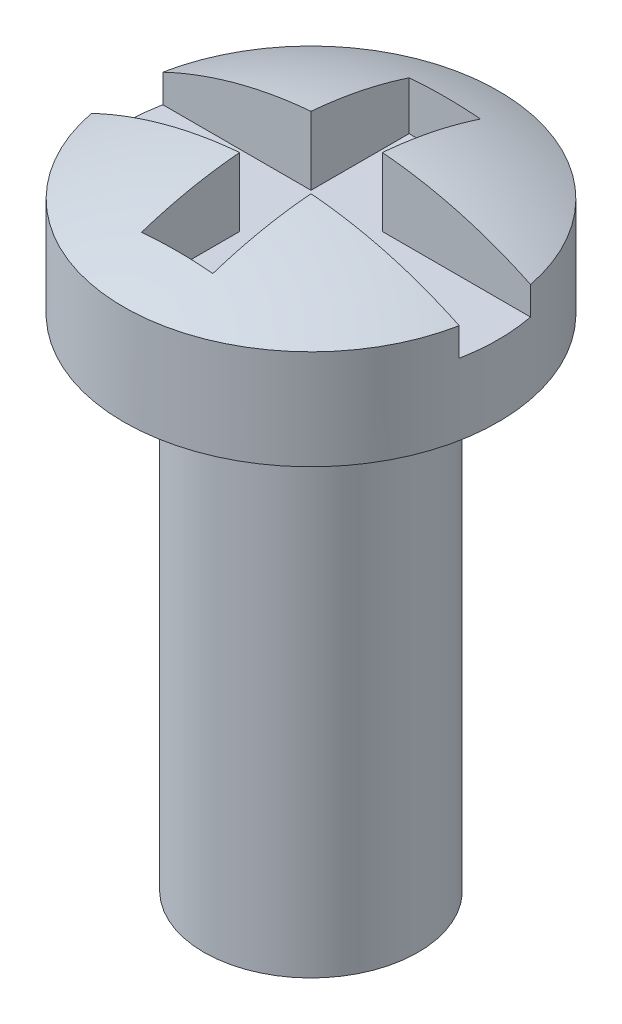
SolidWorks part; units mm, degrees
ref_plane "前视基准面" through (0, 0, 0) normal (0, 0, 1) x (1, 0, 0)
ref_plane "上视基准面" through (0, 0, 0) normal (0, 1, 0) x (1, 0, 0)
ref_plane "右视基准面" through (0, 0, 0) normal (1, 0, 0) x (0, 0, -1)
sketch "草图1" plane through (0, 0, 0) normal (0, 1, 0) x (1, 0, 0)
  circle A0 centre (0, 0) radius 1.5
  dimension "D1" = 3
extrude "拉伸1" add sketch "草图1" along normal blind 7
sketch "草图2" plane through (0, 7, 0) normal (0, 1, 0) x (-1, 0, 0)
  circle A0 centre (0, 0) radius 2.625
  dimension "D1" = 5.25
extrude "拉伸2" add sketch "草图2" along normal blind 2
sketch "草图3" plane through (0, 9, 0) normal (0, 1, 0) x (-1, 0, 0)
  line L0 (4.0624, 0) -> (-4.2778, 0) construction
  line L1 (0, -3.5166) -> (0, 3.738) construction
  line L3 (3.5023, -0.5) -> (-3.5023, -0.5)
  line L4 (3.5023, -0.5) -> (3.5023, 0.5)
  line L5 (3.5023, 0.5) -> (-3.5023, 0.5)
  line L6 (-3.5023, -0.5) -> (-3.5023, 0.5)
  dimension "D1" = 1
extrude "切除-拉伸1" cut sketch "草图3" against normal blind 1
sketch "草图4" plane through (0, 9, 0) normal (0, 1, 0) x (-1, 0, 0)
  line L0 (0, -3.8639) -> (0, 3.6765) construction
  line L1 (1.7727, 0) -> (-1.7019, 0) construction
  line L2 (0.5, -1.875) -> (-0.5, -1.875)
  line L3 (0.5, -1.875) -> (0.5, 1.875)
  line L4 (0.5, 1.875) -> (-0.5, 1.875)
  line L5 (-0.5, -1.875) -> (-0.5, 1.875)
  dimension "D1" = 1
  dimension "D2" = 3.75
extrude "切除-拉伸2" cut sketch "草图4" against normal blind 1
sketch "草图5" plane through (0, 0, 0) normal (1, 0, 0) x (0, 0, -1)
  line L0 (0, -2.1059) -> (0, 12.2815) construction
  line L1 (-0.5, 9) -> (-2.625, 9) construction
  line L2 (0, 10.9998) -> (-4.5494, 10.9998)
  line L3 (-4.5494, 6.9119) -> (-4.5494, 10.9998)
  line L5 (0, 10.9998) -> (0, 9)
  arc A2 (0, 9) -> (-4.5494, 6.9119) centre (0, 3) ccw
  point P9 (0, 0)
  point P10 (0, 0)
  dimension "D1" = 6
revolve "切除-旋转16" cut sketch "草图5" angle 360 about L0
